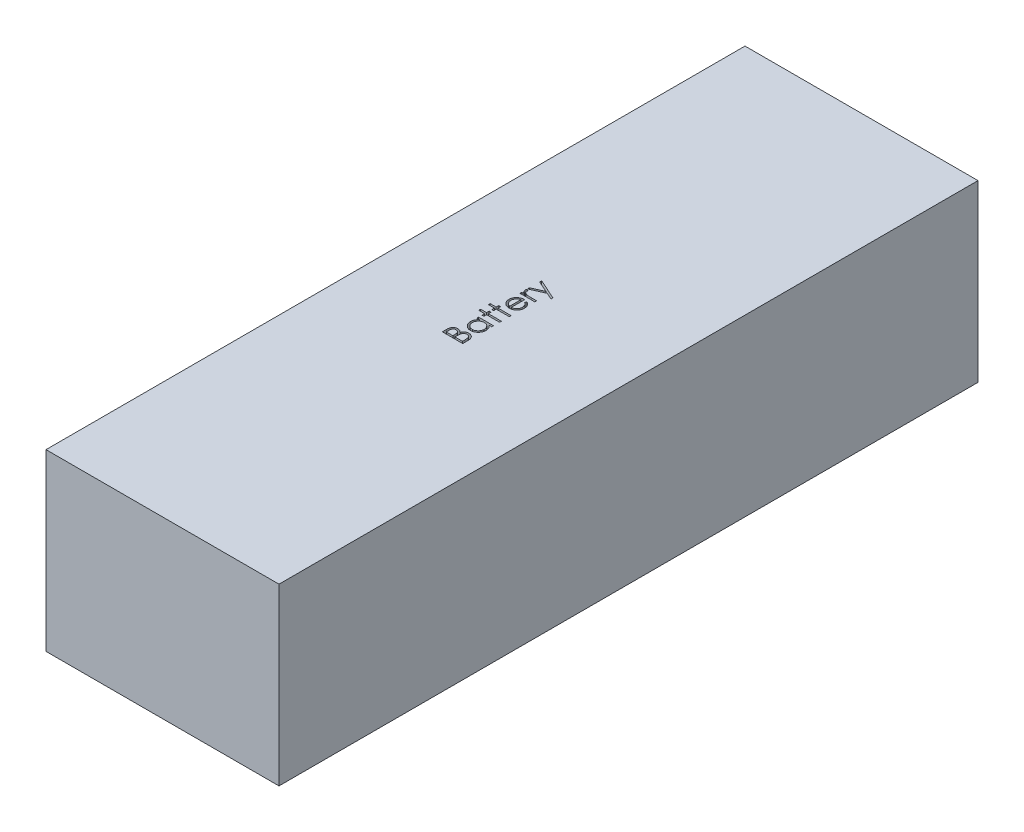
SolidWorks part; units mm, degrees
ref_plane "Front Plane" through (0, 0, 0) normal (0, 0, 1) x (1, 0, 0)
ref_plane "Top Plane" through (0, 0, 0) normal (0, 1, 0) x (1, 0, 0)
ref_plane "Right Plane" through (0, 0, 0) normal (1, 0, 0) x (0, 0, -1)
sketch "Sketch1" plane through (0, 0, 0) normal (0, 1, 0) x (1, 0, 0)
  line L1 (-20, 60) -> (20, 60)
  line L2 (-20, 60) -> (-20, -60)
  line L3 (-20, -60) -> (20, -60)
  line L4 (20, 60) -> (20, -60)
  line L5 (-20, 60) -> (20, -60) construction
  line L6 (-20, -60) -> (20, 60) construction
  point P0 (0, 0)
  dimension "D1" = 40
  dimension "D2" = 120
extrude "Boss-Extrude1" add sketch "Sketch1" along normal blind 30
sketch "Sketch2" plane through (0, 30, 0) normal (0, 1, 0) x (1, 0, 0)
  line L0 (0, -60) -> (0, 60) construction
  line L1 (-20, -60) -> (20, -60) construction
  line L2 (20, 60) -> (-20, 60) construction
  text T0 "Battery " font "Century Gothic" height 3.5
extrude "Cut-Extrude1" cut sketch "Sketch2" against normal blind 2
